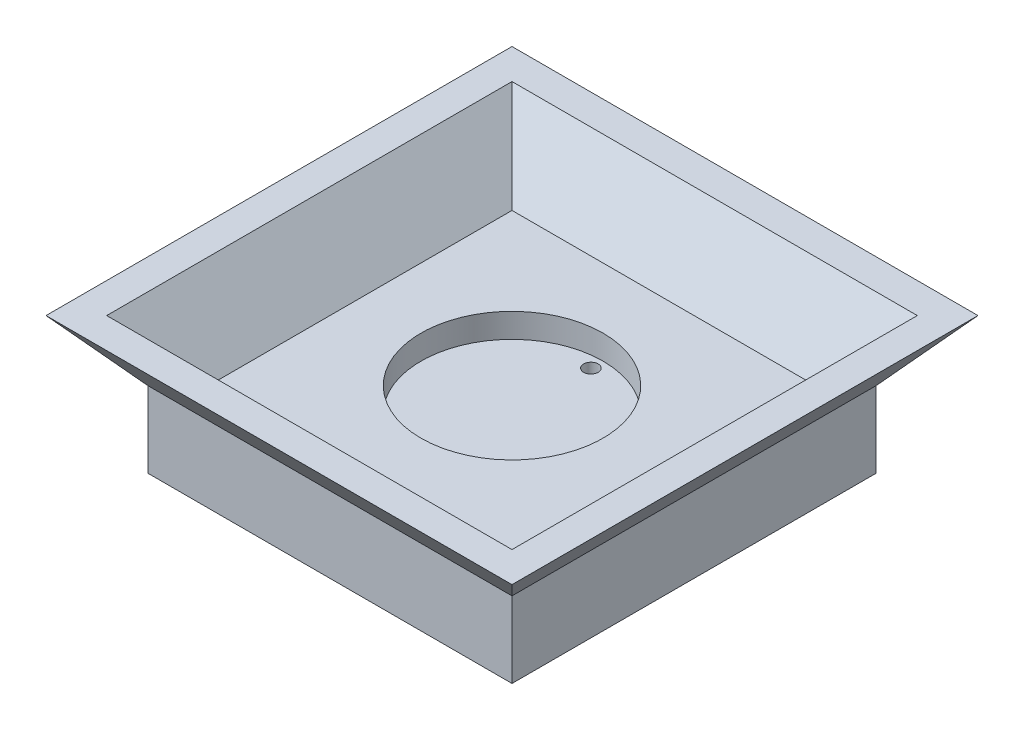
SolidWorks part; units mm, degrees
ref_plane "Front Plane" through (0, 0, 0) normal (0, 0, 1) x (1, 0, 0)
ref_plane "Top Plane" through (0, 0, 0) normal (0, 1, 0) x (1, 0, 0)
ref_plane "Right Plane" through (0, 0, 0) normal (1, 0, 0) x (0, 0, -1)
sketch "Sketch1" plane through (0, 0, 0) normal (0, 1, 0) x (1, 0, 0)
  line L1 (-38.1, -38.1) -> (38.1, -38.1)
  line L2 (-38.1, -38.1) -> (-38.1, 38.1)
  line L3 (-38.1, 38.1) -> (38.1, 38.1)
  line L4 (38.1, -38.1) -> (38.1, 38.1)
  line L5 (-38.1, -38.1) -> (38.1, 38.1) construction
  line L6 (-38.1, 38.1) -> (38.1, -38.1) construction
  point P0 (0, 0)
  dimension "D1" = 76.2
extrude "Boss-Extrude1" add sketch "Sketch1" along normal mid plane 31.75
sketch "Sketch2" plane through (0, 15.875, 0) normal (0, 1, 0) x (1, 0, 0)
  line L0 (-38.1, -38.1) -> (38.1, -38.1) construction
  line L1 (-38.1, 38.1) -> (38.1, 38.1)
  line L2 (-38.1, 38.1) -> (-38.1, -38.1)
  line L3 (-38.1, -38.1) -> (38.1, -38.1)
  line L4 (38.1, 38.1) -> (38.1, -38.1)
extrude "Boss-Extrude2" add sketch "Sketch2" along normal blind 12.7 draft 40 draft outward yes
mirror "Mirror1" about plane through (0, 0, 0) normal (0, 1, 0) of "Boss-Extrude2"
sketch "Sketch4" plane through (0, 28.575, 0) normal (0, 1, 0) x (1, 0, 0)
  line L0 (-42.4066, 25.4201) -> (-48.7566, 25.4201) construction
  line L1 (42.4066, -42.4066) -> (-42.4066, -42.4066)
  line L2 (42.4066, -42.4066) -> (42.4066, 42.4066)
  line L3 (42.4066, 42.4066) -> (-42.4066, 42.4066)
  line L4 (-42.4066, -42.4066) -> (-42.4066, 42.4066)
  line L5 (42.4066, -42.4066) -> (-42.4066, 42.4066) construction
  line L6 (42.4066, 42.4066) -> (-42.4066, -42.4066) construction
  line L7 (-48.7566, 48.7566) -> (-48.7566, -48.7566) construction
  point P0 (0, 0)
  dimension "D1" = 6.35
extrude "Cut-Extrude2" cut sketch "Sketch4" against normal blind 12.7 draft 40
sketch "Sketch5" plane through (0, 15.875, 0) normal (0, 1, 0) x (1, 0, 0)
  circle A0 centre (0, 0) radius 19.05
  dimension "D1" = 38.1
extrude "Cut-Extrude3" cut sketch "Sketch5" against normal blind 5.08
sketch "Sketch6" plane through (0, 10.795, 0) normal (0, 1, 0) x (1, 0, 0)
  line L1 (0, 19.05) -> (0, 13.97) construction
  line L2 (0, 13.97) -> (0, 19.05) construction
  circle A0 centre (0, 0) radius 19.05 construction
  circle A2 centre (0, 16.51) radius 1.524
  dimension "D2" = 3.048
  dimension "D1" = 5.08
extrude "Cut-Extrude4" cut sketch "Sketch6" against normal blind 20.32 contours A2
sketch "Sketch8" plane through (0, 0, 0) normal (0, 1, 0) x (1, 0, 0)
  line L1 (-52.018, 50.4034) -> (58.336, 50.4034)
  line L2 (-52.018, 50.4034) -> (-52.018, -56.5108)
  line L3 (-52.018, -56.5108) -> (58.336, -56.5108)
  line L4 (58.336, 50.4034) -> (58.336, -56.5108)
extrude "Cut-Extrude5" cut sketch "Sketch8" against normal up to next
